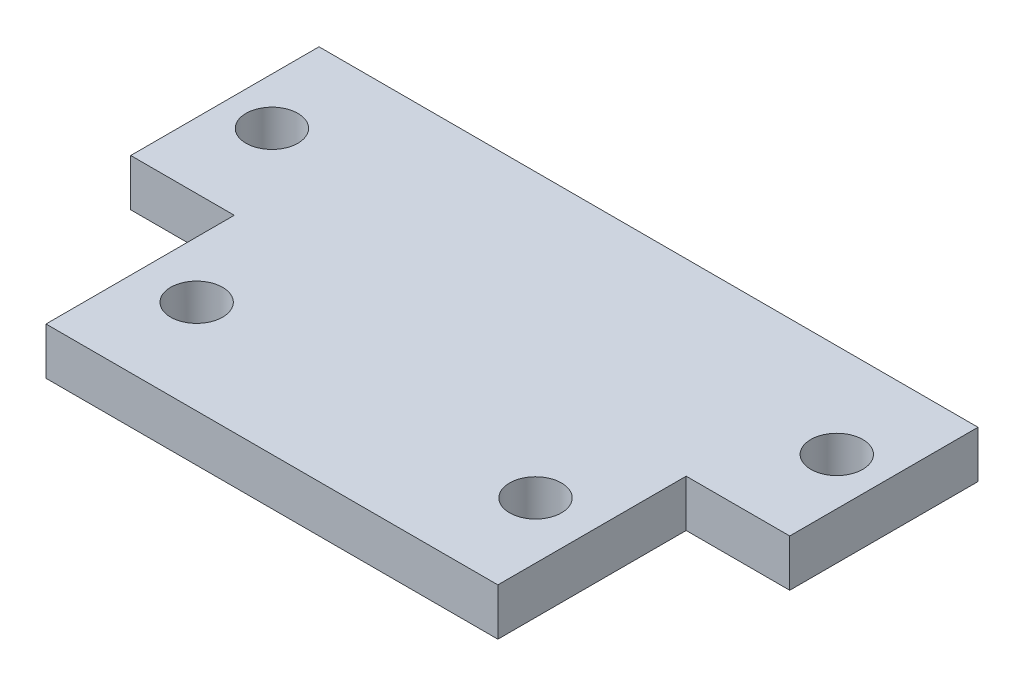
SolidWorks part; units mm, degrees
ref_plane "Front Plane" through (0, 0, 0) normal (1, 0, 0) x (0, 1, 0)
ref_plane "Top Plane" through (0, 0, 0) normal (0, 0, 1) x (0, 1, 0)
ref_plane "Right Plane" through (0, 0, 0) normal (0, 1, 0) x (-1, 0, 0)
sketch "Sketch1" plane through (0, 0, 0) normal (0, 1, 0) x (-1, 0, 0)
  line L1 (19.05, -6.35) -> (-19.05, -6.35) construction
  line L2 (19.05, -6.35) -> (19.05, 6.35) construction
  line L3 (19.05, 6.35) -> (-19.05, 6.35) construction
  line L4 (-19.05, -6.35) -> (-19.05, 6.35) construction
  line L5 (19.05, -6.35) -> (-19.05, 6.35) construction
  line L6 (19.05, 6.35) -> (-19.05, -6.35) construction
  line L7 (7.9375, -6.35) -> (-7.9375, -6.35) construction
  line L8 (7.9375, -6.35) -> (7.9375, 6.35) construction
  line L9 (7.9375, 6.35) -> (-7.9375, 6.35) construction
  line L10 (-7.9375, -6.35) -> (-7.9375, 6.35) construction
  line L11 (7.9375, -6.35) -> (-7.9375, 6.35) construction
  line L12 (7.9375, 6.35) -> (-7.9375, -6.35) construction
  line L13 (22.225, -6.35) -> (-22.225, -6.35)
  line L14 (22.225, -6.35) -> (22.225, 6.35)
  line L15 (22.225, 6.35) -> (-22.225, 6.35)
  line L16 (-22.225, -6.35) -> (-22.225, 6.35)
  line L17 (22.225, -6.35) -> (-22.225, 6.35) construction
  line L18 (22.225, 6.35) -> (-22.225, -6.35) construction
  line L19 (12.7, -3.175) -> (-12.7, -3.175) construction
  line L20 (12.7, -3.175) -> (12.7, 3.175) construction
  line L21 (12.7, 3.175) -> (-12.7, 3.175) construction
  line L22 (-12.7, -3.175) -> (-12.7, 3.175) construction
  line L23 (12.7, -3.175) -> (-12.7, 3.175) construction
  line L24 (12.7, 3.175) -> (-12.7, -3.175) construction
  line L25 (-15.24, 6.35) -> (15.24, 6.35)
  line L26 (-15.24, 6.35) -> (-15.24, 19.05)
  line L27 (-15.24, 19.05) -> (15.24, 19.05)
  line L28 (15.24, 6.35) -> (15.24, 19.05)
  circle A1 centre (19.05, 0) radius 1.75
  circle A2 centre (-19.05, 0) radius 1.75
  circle A5 centre (19.05, 0) radius 9.017 construction
  point P0 (0, 0)
  point P8 (0, 0)
  point P15 (0, 0)
  point P20 (0, 0)
  point P35 (0, 19.05)
  point P36 (0, 19.05)
  dimension "D3" = 3.5
  dimension "D8" = 18.034
  dimension "D1" = 38.1
  dimension "D2" = 12.7
  dimension "D4" = 15.875
  dimension "D5" = 25.4
  dimension "D6" = 6.35
  dimension "D7" = 44.45
  dimension "D9" = 30.48
  dimension "D11" = 12.7
extrude "Boss-Extrude1" add sketch "Sketch1" along normal blind 3.175
sketch "Sketch2" plane through (0, 3.175, 0) normal (0, 1, 0) x (-1, 0, 0)
  line L1 (19.05, -19.05) -> (-19.05, -19.05) construction
  line L2 (19.05, -19.05) -> (19.05, 19.05) construction
  line L3 (19.05, 19.05) -> (-19.05, 19.05) construction
  line L4 (-19.05, -19.05) -> (-19.05, 19.05) construction
  line L5 (19.05, -19.05) -> (-19.05, 19.05) construction
  line L6 (19.05, 19.05) -> (-19.05, -19.05) construction
  line L7 (-6.985, 19.05) -> (6.985, 19.05) construction
  line L8 (-6.985, 19.05) -> (-6.985, 6.35) construction
  line L9 (-6.985, 6.35) -> (6.985, 6.35) construction
  line L10 (6.985, 19.05) -> (6.985, 6.35) construction
  line L11 (-15.24, 6.35) -> (-22.225, 6.35) construction
  line L12 (-15.875, 19.05) -> (-15.875, 6.35) construction
  line L13 (-15.875, 6.35) -> (-6.985, 6.35) construction
  line L14 (0, 6.35) -> (0, 0) construction
  circle A0 centre (-11.43, 12.7) radius 1.75
  circle A1 centre (11.43, 12.7) radius 1.75
  point P0 (0, 0)
  point P13 (0, 6.35)
  point P14 (-11.43, 6.35)
  dimension "D5" = 3.5
  dimension "D1" = 38.1
  dimension "D2" = 8.89
  dimension "D3" = 3.175
  dimension "D4" = 6.35
extrude "Cut-Extrude1" cut sketch "Sketch2" against normal blind 12.192
